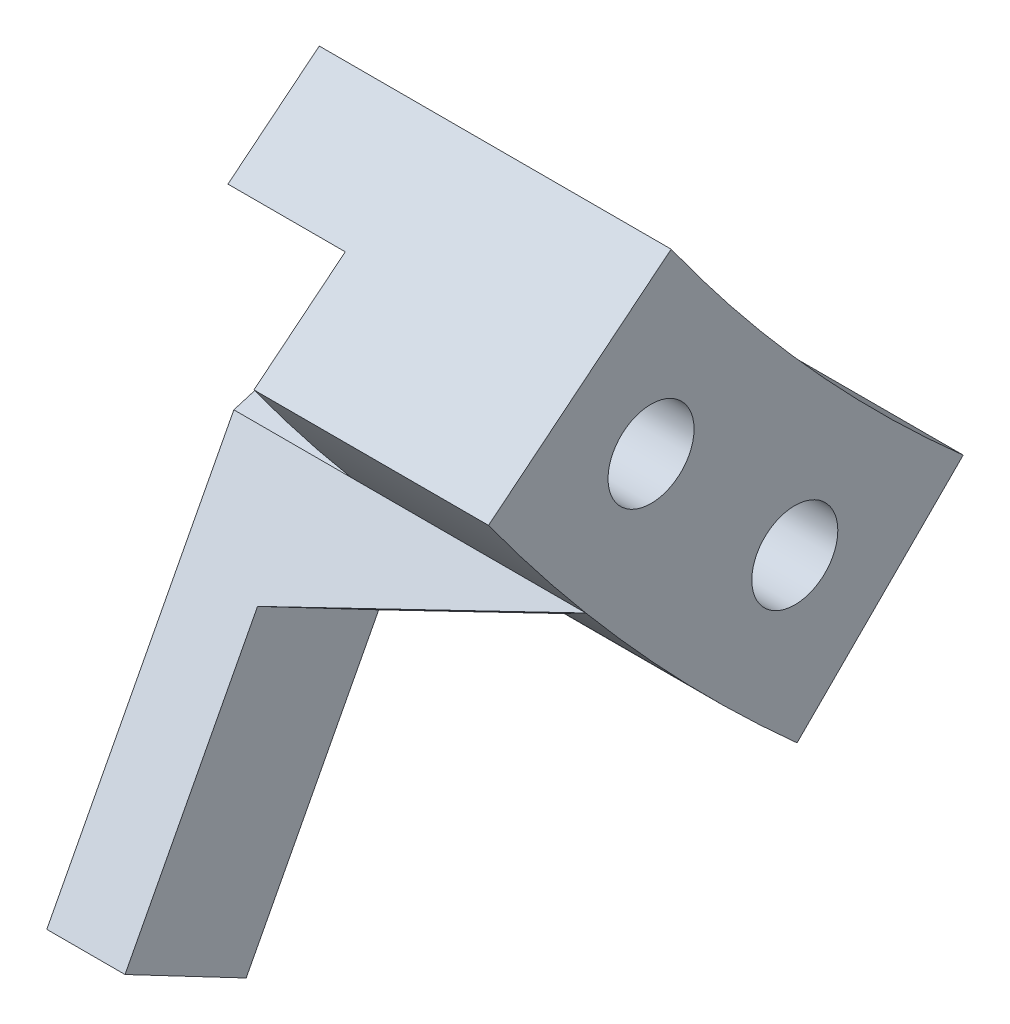
SolidWorks part; units mm, degrees
material "PLA"
ref_plane "前视基准面" through (0, 0, 0) normal (0, 0, 1) x (1, 0, 0)
ref_plane "上视基准面" through (0, 0, 0) normal (0, 1, 0) x (1, 0, 0)
ref_plane "右视基准面" through (0, 0, 0) normal (1, 0, 0) x (0, 0, -1)
sketch "草图1" plane through (0, 0, 0) normal (1, 0, 0) x (0, 0, -1)
  line L0 (0, 0) -> (-37.1231, -37.1231) construction
  line L1 (0, 0) -> (-40.8002, -33.0393) construction
  line L2 (0, 0) -> (0, -33.0167) construction
  line L3 (-11.3096, 23.2958) -> (-46.2796, -52.8492) construction
  line L4 (-44.9565, -32.5448) -> (-40.286, -28.7627)
  line L5 (-32.8161, -37.0588) -> (-37.0657, -41.3084)
  circle A0 centre (0, 0) radius 52.5 construction
  circle A1 centre (-40.8002, -33.0393) radius 1.1
  circle A2 centre (-37.1231, -37.1231) radius 1.1
  arc A3 (-40.286, -28.7627) -> (-32.8161, -37.0588) centre (0, 0) ccw
  arc A4 (-44.9565, -32.5448) -> (-37.0657, -41.3084) centre (0, 0) ccw
  dimension "D1" = 105
  dimension "D4" = 2.2
  dimension "D5" = 3
  dimension "D6" = 3
  dimension "D2" = 45
  dimension "D3" = 6
  dimension "D7" = 20
  dimension "D8" = 3
  dimension "D9" = 3
extrude "凸台-拉伸1" add sketch "草图1" along normal blind 9
sketch "草图2" plane through (0, 0, 0) normal (-1, 0, 0) x (0, 0, 1)
  line L0 (11.0065, 16.6853) -> (48.7518, -55.229) construction
  line L1 (42.4698, -35.7291) -> (47.2544, -44.8449)
  line L2 (47.2544, -44.8449) -> (44.1553, -46.4715)
  line L3 (44.1553, -46.4715) -> (39.9726, -38.5024)
  line L4 (36.7857, -33.122) -> (41.2445, -37.1367) construction
  arc A0 (37.0657, -41.3084) -> (44.9565, -32.5448) centre (0, 0) ccw construction
  arc A1 (32.8161, -37.0588) -> (40.286, -28.7627) centre (0, 0) ccw construction
  arc A2 (39.9726, -38.5024) -> (42.4698, -35.7291) centre (0, 0) ccw
  dimension "D1" = 17.5
  dimension "D2" = 9
  dimension "D3" = 3.5
extrude "凸台-拉伸2" add sketch "草图2" against normal blind 2
sketch "草图3" plane through (0, 9.7596, 18.5944) normal (0, 0.4647, 0.8854) x (1, 0, 0)
  line L0 (2, -51.3736) -> (2, -54.3736)
  line L1 (2, -61.6688) -> (2, -51.3736) construction
  line L2 (2, -54.3736) -> (9, -51.3736)
  line L3 (9, -51.3736) -> (2, -51.3736)
  line L4 (9, -53.8023) -> (9, -49.7098) construction
  dimension "D2" = 3
extrude "凸台-拉伸3" add sketch "草图3" against normal up to surface (3.5 mm away) up to face at (1, -42.487, 42.064)
sketch "草图4" plane through (0, 0, 0) normal (-1, 0, 0) x (0, 0, 1)
  line L0 (40.8002, -30.9393) -> (42.6212, -30.6537)
  line L1 (40.286, -28.7627) -> (44.9565, -32.5448) construction
  line L2 (42.4698, -35.7291) -> (40.1997, -35.0516)
  line L3 (34.9409, -39.1836) -> (35.0231, -37.1231)
  line L4 (37.0657, -41.3084) -> (32.8161, -37.0588) construction
  line L5 (39.0616, -36.3156) -> (39.9726, -38.5024)
  line L6 (42.6212, -30.6537) -> (44.9565, -32.5448)
  line L7 (37.0657, -41.3084) -> (34.9409, -39.1836)
  arc A0 (40.8002, -30.9393) -> (40.1997, -35.0516) centre (40.8002, -33.0393) ccw
  arc A1 (39.0616, -36.3156) -> (35.0231, -37.1231) centre (37.1231, -37.1231) ccw
  arc A2 (42.4698, -35.7291) -> (44.9565, -32.5448) centre (0, 0) ccw construction
  arc A3 (37.0657, -41.3084) -> (39.9726, -38.5024) centre (0, 0) ccw construction
  arc A4 (42.4698, -35.7291) -> (44.9565, -32.5448) centre (0, 0) ccw
  arc A5 (37.0657, -41.3084) -> (39.9726, -38.5024) centre (0, 0) ccw
  dimension "D1" = 4.2
extrude "切除-拉伸1" cut sketch "草图4" against normal blind 3
